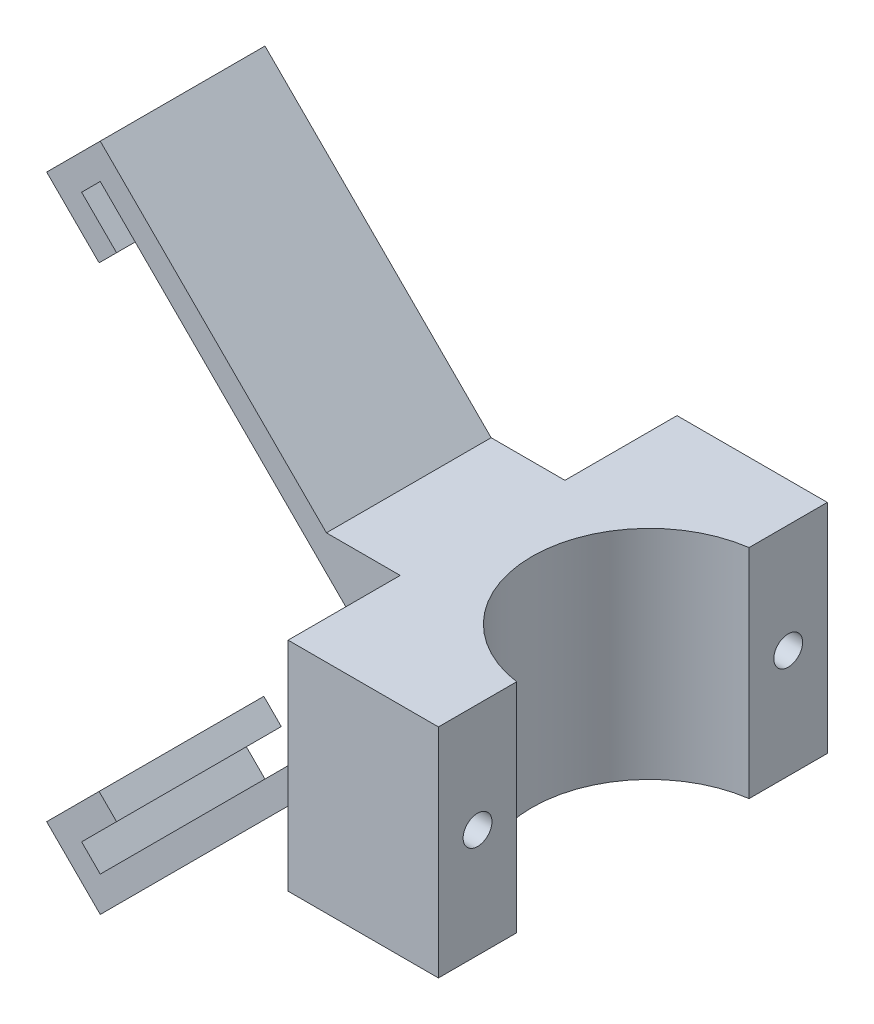
SolidWorks part; units mm, degrees
ref_plane "Front Plane" through (0, 0, 0) normal (0, 0, 1) x (1, 0, 0)
ref_plane "Top Plane" through (0, 0, 0) normal (0, 1, 0) x (1, 0, 0)
ref_plane "Right Plane" through (0, 0, 0) normal (1, 0, 0) x (0, 0, -1)
sketch "Sketch1" plane through (0, 0, 0) normal (0, 1, 0) x (1, 0, 0)
  line L0 (0, 23.609) -> (0, -23.609)
  line L1 (0, 23.609) -> (18.25, 23.609)
  line L2 (18.25, 23.609) -> (18.25, 14.109)
  line L3 (18.25, -23.609) -> (0, -23.609)
  line L5 (18.25, -14.109) -> (18.25, -23.609)
  arc A2 (18.25, -14.109) -> (18.25, 14.109) centre (20.25, 0) cw
  dimension "D1" = 6
  dimension "D3" = 14.25
  dimension "D4" = 9.5
  dimension "D7" = 2
extrude "Boss-Extrude1" add sketch "Sketch1" along normal blind 26.4
sketch "Sketch2" plane through (18.25, 0, 0) normal (1, 0, 0) x (0, 0, -1)
  line L0 (-23.609, 26.4) -> (-14.109, 26.4) construction
  line L1 (-23.609, 26.4) -> (-23.609, 0) construction
  circle A0 centre (-18.859, 13.2) radius 1.75
  point P4 (-18.859, 26.4)
  point P7 (-23.609, 13.2)
  dimension "D1" = 3.5
extrude "Cut-Extrude1" cut sketch "Sketch2" against normal through all
sketch "Sketch5" plane through (18.25, 0, 0) normal (1, 0, 0) x (0, 0, -1)
  line L1 (-17.2424, 16) -> (-20.4755, 16)
  line L2 (-20.4755, 16) -> (-22.0921, 13.2)
  line L3 (-22.0921, 13.2) -> (-20.4755, 10.4)
  line L4 (-20.4755, 10.4) -> (-17.2424, 10.4)
  line L5 (-17.2424, 10.4) -> (-15.6258, 13.2)
  line L6 (-15.6258, 13.2) -> (-17.2424, 16)
  circle A0 centre (-18.859, 13.2) radius 2.8 construction
  dimension "D1" = 5.6
extrude "Cut-Extrude3" cut sketch "Sketch5" against normal through all from offset 10 offset against normal yes
mirror "Mirror1" about plane through (0, 0, 0) normal (0, 0, 1) of "Cut-Extrude1", "Cut-Extrude3"
sketch "Sketch7" plane through (0, 0, 0) normal (0, 0, 1) x (1, 0, 0)
  line L0 (0, 0) -> (-8.9574, 0)
  line L1 (-8.9574, 0) -> (-36.416, -27.4586)
  line L2 (-36.416, -27.4586) -> (-42.9214, -20.9533)
  line L3 (-42.9214, -20.9533) -> (-36.5574, -14.5893)
  line L4 (-36.5574, -14.5893) -> (-34.4361, -16.7106)
  line L5 (-38.6787, -20.9533) -> (-34.4361, -16.7106)
  line L6 (-38.6787, 47.3533) -> (-36.416, 49.616)
  line L7 (-36.416, -23.216) -> (0, 13.2)
  line L8 (0, 26.4) -> (0, 0) construction
  line L9 (0, 13.2) -> (-36.416, 49.616)
  line L10 (-38.6787, -20.9533) -> (-36.416, -23.216)
  line L11 (-38.6787, 47.3533) -> (-34.4361, 43.1106)
  line L12 (-34.4361, 43.1106) -> (-36.5574, 40.9893)
  line L13 (-36.5574, 40.9893) -> (-42.9214, 47.3533)
  line L14 (-42.9214, 47.3533) -> (-36.416, 53.8586)
  line L15 (-36.416, 53.8586) -> (-8.9574, 26.4)
  line L16 (-8.9574, 26.4) -> (0, 26.4)
  line L17 (0, 26.4) -> (6, 26.4)
  line L18 (0, 26.4) -> (18.25, 26.4) construction
  line L19 (6, 26.4) -> (6, 0)
  line L20 (0, 0) -> (18.25, 0) construction
  line L21 (6, 0) -> (0, 0)
  line L22 (-38.5373, 51.7373) -> (-36.416, 49.616) construction
  line L23 (-36.416, 49.616) -> (-34.2947, 51.7373) construction
  line L24 (-38.5373, -25.3373) -> (-36.416, -23.216) construction
  line L25 (-36.416, -23.216) -> (-34.2947, -25.3373) construction
  dimension "D1" = 6
  dimension "D2" = 3
  dimension "D3" = 3.2
  dimension "D4" = 51.5
extrude "Boss-Extrude2" add sketch "Sketch7" along normal mid plane 20
